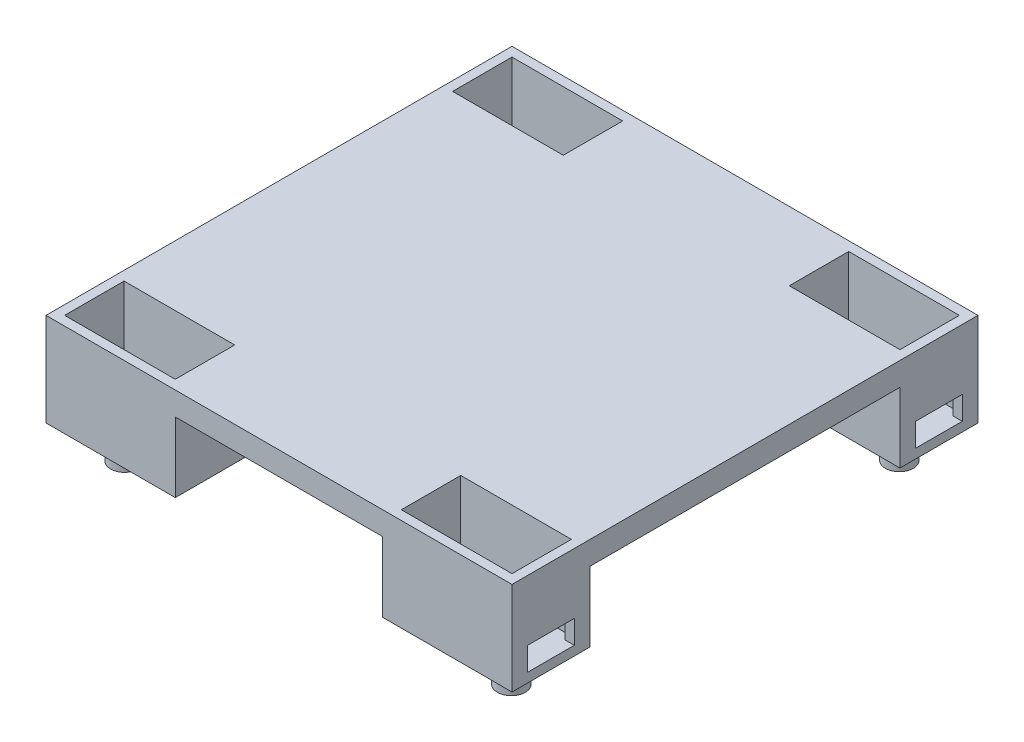
SolidWorks part; units mm, degrees
ref_plane "Front Plane" through (0, 0, 0) normal (0, 0, 1) x (1, 0, 0)
ref_plane "Top Plane" through (0, 0, 0) normal (0, 1, 0) x (1, 0, 0)
ref_plane "Right Plane" through (0, 0, 0) normal (1, 0, 0) x (0, 0, -1)
sketch "Sketch1" plane through (0, 0, 0) normal (0, 1, 0) x (1, 0, 0)
  line L0 (0, 50) -> (0, -50) construction
  line L5 (-50, -50) -> (50, -50)
  line L6 (-50, -50) -> (-50, 50)
  line L7 (-50, 50) -> (50, 50)
  line L8 (50, -50) -> (50, 50)
  line L9 (-50, -50) -> (50, 50) construction
  line L10 (-50, 50) -> (50, -50) construction
  line L25 (-50, 0) -> (50, 0) construction
  point P0 (0, 0)
  dimension "D1" = 100
  dimension "D2" = 100
extrude "Boss-Extrude1" add sketch "Sketch1" along normal blind 2 and the other way blind 3
sketch "Sketch3" plane through (0, 0, 0) normal (0, 1, 0) x (1, 0, 0)
  line L0 (-50, -50) -> (50, -50) construction
  line L1 (-50, -50) -> (-22.25, -50)
  line L2 (-50, -50) -> (-50, -33.25)
  line L3 (-50, -33.25) -> (-22.25, -33.25)
  line L4 (-22.25, -50) -> (-22.25, -33.25)
  line L5 (-50, -50) -> (-22.25, -33.25) construction
  line L6 (-50, -33.25) -> (-22.25, -50) construction
  line L7 (-50, -50) -> (-50, 50) construction
  line L8 (0, 50) -> (0, -50) construction
  line L9 (-50, 50) -> (50, 50) construction
  line L10 (50, 0) -> (-50, 0) construction
  line L12 (50, -50) -> (50, 50) construction
  line L13 (50, -50) -> (22.25, -33.25) construction
  line L14 (50, -33.25) -> (22.25, -50) construction
  line L15 (50, -50) -> (22.25, -50)
  line L16 (22.25, -50) -> (22.25, -33.25)
  line L17 (50, -33.25) -> (22.25, -33.25)
  line L18 (50, -50) -> (50, -33.25)
  line L19 (50, 33.25) -> (22.25, 50) construction
  line L20 (50, 50) -> (22.25, 33.25) construction
  line L21 (-50, 33.25) -> (-22.25, 50) construction
  line L22 (-50, 50) -> (-22.25, 33.25) construction
  line L23 (50, 50) -> (50, 33.25)
  line L24 (50, 33.25) -> (22.25, 33.25)
  line L25 (22.25, 50) -> (22.25, 33.25)
  line L26 (50, 50) -> (22.25, 50)
  line L27 (-22.25, 50) -> (-22.25, 33.25)
  line L28 (-50, 33.25) -> (-22.25, 33.25)
  line L29 (-50, 50) -> (-50, 33.25)
  line L30 (-50, 50) -> (-22.25, 50)
  point P0 (-36.125, -41.625)
  point P17 (36.125, -41.625)
  point P30 (36.125, 41.625)
  point P31 (-36.125, 41.625)
  point P32 (0, 0)
  dimension "D3" = 16.75
  dimension "27.75" = 27.75
extrude "Boss-Extrude4" add sketch "Sketch3" against normal blind 18
ref_plane "Plane3" through (0, 2, 0) normal (0, 1, 0) x (1, 0, 0)
sketch "Sketch4" plane through (0, 2, 0) normal (0, 1, 0) x (1, 0, 0)
  line L0 (-50, 0) -> (50, 0) construction
  line L1 (-50, -50) -> (-50, 50) construction
  line L2 (50, -50) -> (50, 50) construction
  line L3 (0, 50) -> (0, -50) construction
  line L4 (-50, 50) -> (50, 50) construction
  line L5 (-50, -50) -> (50, -50) construction
  line L6 (48, -48) -> (24.25, -35.25) construction
  line L7 (-48, -48) -> (-24.25, -48)
  line L8 (-48, -48) -> (-48, -35.25)
  line L9 (-48, -35.25) -> (-24.25, -35.25)
  line L10 (-24.25, -48) -> (-24.25, -35.25)
  line L11 (-48, -48) -> (-24.25, -35.25) construction
  line L12 (-48, -35.25) -> (-24.25, -48) construction
  line L13 (48, -35.25) -> (24.25, -48) construction
  line L14 (48, -35.25) -> (24.25, -35.25)
  line L15 (24.25, -48) -> (24.25, -35.25)
  line L16 (48, -48) -> (24.25, -48)
  line L17 (48, -48) -> (48, -35.25)
  line L18 (48, 35.25) -> (24.25, 48) construction
  line L19 (-48, 35.25) -> (-24.25, 48) construction
  line L20 (-48, 48) -> (-24.25, 35.25) construction
  line L21 (48, 48) -> (24.25, 35.25) construction
  line L22 (48, 48) -> (48, 35.25)
  line L23 (48, 48) -> (24.25, 48)
  line L24 (24.25, 48) -> (24.25, 35.25)
  line L25 (48, 35.25) -> (24.25, 35.25)
  line L26 (-24.25, 48) -> (-24.25, 35.25)
  line L27 (-48, 35.25) -> (-24.25, 35.25)
  line L28 (-48, 48) -> (-48, 35.25)
  line L29 (-48, 48) -> (-24.25, 48)
  point P13 (-36.125, -41.625)
  point P18 (36.125, -41.625)
  point P31 (36.125, 41.625)
  point P32 (-36.125, 41.625)
  dimension "D1" = 2
  dimension "D2" = 2
  dimension "D3" = 12.75
  dimension "D4" = 23.75
extrude "Cut-Extrude1" cut sketch "Sketch4" against normal blind 18
ref_plane "Plane4" through (0, -18, 0) normal (0, -1, 0) x (-1, 0, 0)
sketch "Sketch5" plane through (0, -18, 0) normal (0, -1, 0) x (-1, 0, 0)
  line L0 (0, -50) -> (0, 50) construction
  line L1 (22.25, -50) -> (-22.25, -50) construction
  line L2 (22.25, 50) -> (-22.25, 50) construction
  line L3 (-50, 0) -> (50, 0) construction
  line L4 (-50, -33.25) -> (-50, 33.25) construction
  line L5 (50, -33.25) -> (50, 33.25) construction
  line L6 (50, -33.25) -> (50, -50) construction
  line L7 (50, -50) -> (22.25, -50) construction
  circle A0 centre (41.5, -41.625) radius 3
  circle A1 centre (-41.5, -41.625) radius 3
  circle A2 centre (41.5, 41.625) radius 3
  circle A3 centre (-41.5, 41.625) radius 3
  dimension "D1" = 8.5
  dimension "D2" = 8.375
extrude "Boss-Extrude5" add sketch "Sketch5" along normal blind 7
ref_plane "Plane5" through (50, 0, 0) normal (1, 0, 0) x (0, 0, -1)
sketch "Sketch6" plane through (50, 0, 0) normal (1, 0, 0) x (0, 0, -1)
  line L1 (-46.625, -16) -> (-36.625, -16)
  line L2 (-46.625, -16) -> (-46.625, -11)
  line L3 (-46.625, -11) -> (-36.625, -11)
  line L4 (-36.625, -16) -> (-36.625, -11)
  line L5 (-46.625, -16) -> (-36.625, -11) construction
  line L6 (-46.625, -11) -> (-36.625, -16) construction
  line L10 (-50, -18) -> (-50, 2) construction
  line L11 (0, 0) -> (0, -36.0258) construction
  line L12 (46.625, -11) -> (36.625, -11)
  line L13 (36.625, -16) -> (36.625, -11)
  line L14 (46.625, -16) -> (36.625, -16)
  line L15 (46.625, -16) -> (46.625, -11)
  line L17 (-50, -18) -> (-33.25, -18) construction
  point P0 (-41.625, -13.5)
  dimension "D1" = 5
  dimension "D2" = 10
  dimension "D3" = 2
  dimension "D4" = 3.375
extrude "Cut-Extrude2" cut sketch "Sketch6" against normal blind 2
ref_plane "Plane6" through (-50, 0, 0) normal (-1, 0, 0) x (0, 0, 1)
sketch "Sketch7" plane through (-50, 0, 0) normal (-1, 0, 0) x (0, 0, 1)
  line L0 (0, 0) -> (0, -43.3376) construction
  line L6 (46.625, -16) -> (46.625, -11)
  line L7 (46.625, -11) -> (36.625, -11)
  line L8 (36.625, -16) -> (36.625, -11)
  line L9 (-36.625, -16) -> (-36.625, -11)
  line L10 (-46.625, -11) -> (-36.625, -11)
  line L11 (-46.625, -16) -> (-46.625, -11)
  line L12 (-46.625, -16) -> (-36.625, -16)
  line L14 (36.625, -16) -> (46.625, -16)
extrude "Cut-Extrude3" cut sketch "Sketch7" against normal blind 2
